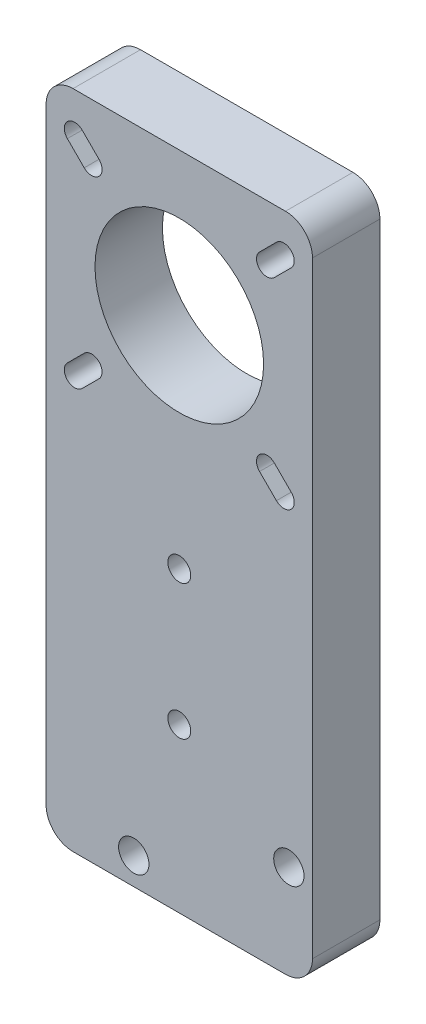
SolidWorks part; units mm, degrees
ref_plane "Front Plane" through (0, 0, 0) normal (0, 0, 1) x (1, 0, 0)
ref_plane "Top Plane" through (0, 0, 0) normal (0, 1, 0) x (1, 0, 0)
ref_plane "Right Plane" through (0, 0, 0) normal (1, 0, 0) x (0, 0, -1)
sketch "Sketch1" plane through (0, 0, 0) normal (0, 0, 1) x (1, 0, 0)
  line L0 (0, 27.75) -> (30, 27.75) construction
  line L1 (15.75, -49) -> (-15.75, -49)
  line L2 (19.75, -45) -> (19.75, 45)
  line L3 (15.75, 49) -> (-15.75, 49)
  line L4 (-19.75, -45) -> (-19.75, 45)
  line L5 (0, 49) -> (0, 27.75) construction
  line L6 (13, 40.75) -> (15.5, 43.25) construction
  line L7 (11.904, 41.846) -> (14.404, 44.346)
  line L8 (14.096, 39.654) -> (16.596, 42.154)
  line L10 (-13, 40.75) -> (-15.5, 43.25) construction
  line L11 (-11.904, 41.846) -> (-14.404, 44.346)
  line L12 (-14.096, 39.654) -> (-16.596, 42.154)
  line L13 (-13, 14.75) -> (-15.5, 12.25) construction
  line L14 (-11.904, 13.654) -> (-14.404, 11.154)
  line L15 (-14.096, 15.846) -> (-16.596, 13.346)
  line L16 (13, 14.75) -> (15.5, 12.25) construction
  line L17 (11.904, 13.654) -> (14.404, 11.154)
  line L18 (14.096, 15.846) -> (16.596, 13.346)
  line L22 (0, 27.75) -> (22.992, 50.742) construction
  arc A0 (-15.75, -49) -> (-19.75, -45) centre (-15.75, -45) cw
  arc A1 (15.75, -49) -> (19.75, -45) centre (15.75, -45) ccw
  arc A2 (19.75, 45) -> (15.75, 49) centre (15.75, 45) ccw
  arc A3 (-15.75, 49) -> (-19.75, 45) centre (-15.75, 45) ccw
  circle A4 centre (0, 27.75) radius 12.5
  arc A5 (11.904, 41.846) -> (14.096, 39.654) centre (13, 40.75) ccw
  arc A6 (16.596, 42.154) -> (14.404, 44.346) centre (15.5, 43.25) ccw
  circle A9 centre (0, -24.8) radius 2.55
  circle A10 centre (0, -4.8) radius 2.55
  arc A13 (-11.904, 41.846) -> (-14.096, 39.654) centre (-13, 40.75) cw
  arc A14 (-16.596, 42.154) -> (-14.404, 44.346) centre (-15.5, 43.25) cw
  arc A15 (-11.904, 13.654) -> (-14.096, 15.846) centre (-13, 14.75) ccw
  arc A16 (-16.596, 13.346) -> (-14.404, 11.154) centre (-15.5, 12.25) ccw
  arc A17 (11.904, 13.654) -> (14.096, 15.846) centre (13, 14.75) cw
  arc A18 (16.596, 13.346) -> (14.404, 11.154) centre (15.5, 12.25) cw
  point P4 (14.25, 42)
  point P40 (-14.25, 42)
  point P47 (-14.25, 13.5)
  point P54 (14.25, 13.5)
  point P59 (-19.75, 0)
  point P60 (0, -49)
  dimension "D2" = 4
  dimension "D3" = 21.25
  dimension "D5" = 3.1
  dimension "D7" = 20
  dimension "D10" = 5.1
  dimension "D4" = 25
  dimension "D8" = 5.1
  dimension "D14" = 8.25
  dimension "D6" = 32.55
  dimension "D1" = 98
  dimension "D9" = 39.5
  dimension "D13" = 5.75
  dimension "D16" = 45
extrude "Boss-Extrude1" add sketch "Sketch1" along normal blind 10 contours A10 | A9 | L3 A3 L4 A0 L1 A1 L2 A2 A16 L15 A15 L14 A10 A9 A6 L8 A5 L7 A4 L12 A14 L11 A13 L18 A18 L17 A17
hole_wizard "Chambrage pour vis à tête ronde bombée M31" positions "Esquisse1" profile "Esquisse3" counterbore size "M3" standard "Ansi Metric" end condition through all
sketch "Esquisse1" plane through (0, 0, 0) normal (0, 0, 1) x (1, 0, 0)
  point P0 (0, -4.8)
  point P3 (0, -24.8)
sketch "Esquisse3" plane through (0, -4.8, 0) normal (1, 0, 0) x (0, 1, 0)
  line L0 (0, 0) -> (0, 10)
  line L1 (0, 10) -> (1.7, 10)
  line L3 (1.7, 10) -> (1.7, 3.5)
  line L4 (1.7, 3.5) -> (3.5, 3.5)
  line L5 (3.5, 3.5) -> (3.5, 0)
  line L7 (3.5, 0) -> (0, 0)
  line L11 (0, -6.35) -> (0, 107.95) construction
  dimension "Diamètre du perçage jusqu'au prochain" = 3.4
  dimension "Profondeur du perçage jusqu'au prochain" = 10
  dimension "Diamètre du chambrage" = 7
  dimension "Profondeur du chambrage" = 3.5
hole_wizard "Diamètre du perçage Ø4.5 (4.5)1" positions "Esquisse4" profile "Esquisse5" hole size "Ø4.5" standard "Ansi Metric" end condition through all
sketch "Esquisse4" plane through (0, 0, 0) normal (0, 0, -1) x (-1, 0, 0)
  circle A0 centre (0, 27.75) radius 12.5 construction
  point P0 (-16.25, -35)
  point P2 (6.75, -45)
  dimension "D3" = 62.75
  dimension "D4" = 16.25
  dimension "D1" = 10
  dimension "D2" = 23
sketch "Esquisse5" plane through (16.25, -35, 0) normal (1, 0, 0) x (0, 1, 0)
  line L0 (0, 0) -> (0, 10)
  line L1 (0, 10) -> (2.25, 10)
  line L2 (2.25, 10) -> (2.25, 0)
  line L5 (2.25, 0) -> (0, 0)
  line L11 (0, -6.35) -> (0, 107.95) construction
  dimension "Diamètre du perçage jusqu'au prochain" = 4.5
  dimension "Profondeur du perçage jusqu'au prochain" = 10
